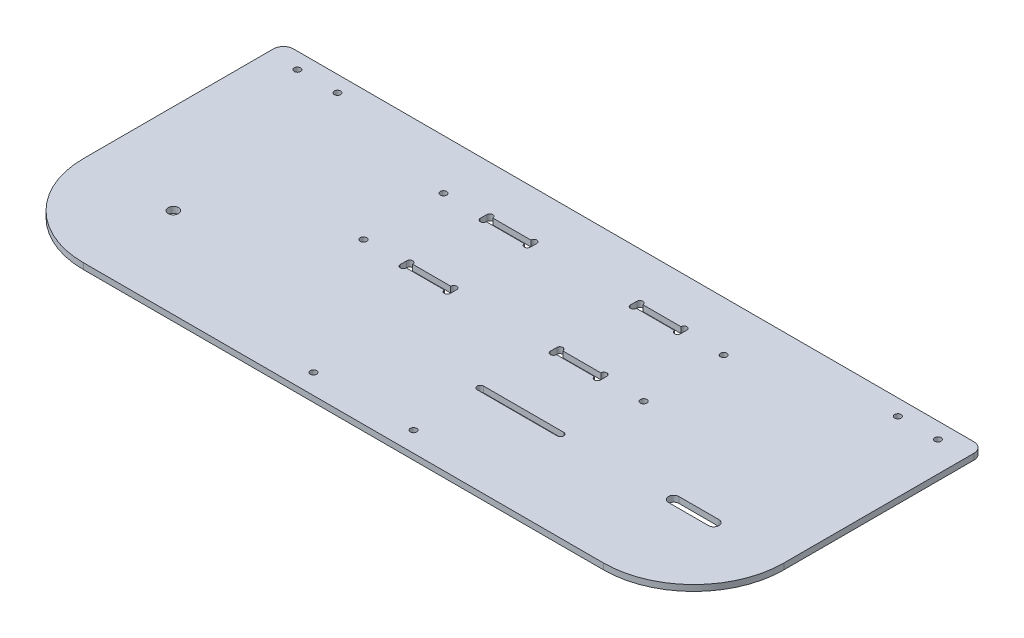
SolidWorks part; units mm, degrees
ref_plane "Front Plane" through (0, 0, 0) normal (0, 0, 1) x (1, 0, 0)
ref_plane "Top Plane" through (0, 0, 0) normal (0, 1, 0) x (1, 0, 0)
ref_plane "Right Plane" through (0, 0, 0) normal (1, 0, 0) x (0, 0, -1)
sketch "Sketch1" plane through (0, 0, 0) normal (0, 1, 0) x (1, 0, 0)
  line L0 (0, 0) -> (260, 0) construction
  line L5 (0, 45) -> (260, 45)
  line L6 (0, -45) -> (260, -45)
  line L7 (270, 0) -> (250, 0) construction
  line L8 (270, -2.6) -> (250, -2.6)
  line L9 (270, 2.6) -> (250, 2.6)
  line L11 (-45, 0) -> (305, 0) construction
  line L12 (-45, 0) -> (-45, 100)
  line L13 (-45, 100) -> (305, 100)
  line L14 (305, 0) -> (305, 100)
  arc A0 (0, 45) -> (0, -45) centre (0, 0) ccw
  arc A1 (260, -45) -> (260, 45) centre (260, 0) ccw
  circle A2 centre (0, 0) radius 2.6
  arc A4 (270, -2.6) -> (270, 2.6) centre (270, 0) ccw
  arc A5 (250, 2.6) -> (250, -2.6) centre (250, 0) ccw
  point P2 (130, 0)
  point P12 (260, 0)
  dimension "D2" = 45
  dimension "D3" = 5.2
  dimension "D1" = 260
  dimension "D4" = 20
  dimension "D5" = 100
  dimension "D6" = 270
extrude "Boss-Extrude1" add sketch "Sketch1" along normal blind 3 contours L6 A1 L5 A0 A5 L9 A4 L8 A2 | A1 L14 L13 L12 A0 L5
sketch "Sketch2" plane through (0, 0, 0) normal (0, -1, 0) x (1, 0, 0)
  line L0 (130, 45) -> (130, -100) construction
  line L1 (80, -73.4) -> (105, -73.4)
  line L2 (80, -73.4) -> (80, -76.6)
  line L3 (80, -76.6) -> (105, -76.6)
  line L4 (105, -73.4) -> (105, -76.6)
  line L5 (0, 45) -> (260, 45) construction
  line L6 (-45, -100) -> (305, -100) construction
  line L7 (-45, -75) -> (305, -75) construction
  line L8 (-45, 0) -> (-45, -100) construction
  line L9 (305, 0) -> (305, -100) construction
  line L10 (81.5, -73.4) -> (81.5, -76.6) construction
  line L11 (83, -73.4) -> (83, -76.6)
  line L12 (80, -73.4) -> (80, -76.6)
  line L13 (103.5, -73.4) -> (103.5, -76.6) construction
  line L14 (105, -73.4) -> (105, -76.6)
  line L15 (102, -73.4) -> (102, -76.6)
  line L16 (-45, -55) -> (305, -55) construction
  line L17 (156.5, -73.4) -> (156.5, -76.6) construction
  line L18 (155, -73.4) -> (155, -76.6)
  line L19 (158, -73.4) -> (158, -76.6)
  line L20 (180, -76.6) -> (155, -76.6)
  line L21 (180, -73.4) -> (155, -73.4)
  line L22 (178.5, -73.4) -> (178.5, -76.6) construction
  line L23 (177, -73.4) -> (177, -76.6)
  line L24 (180, -73.4) -> (180, -76.6)
  line L25 (180, -33.4) -> (155, -33.4)
  line L26 (81.5, -36.6) -> (81.5, -33.4) construction
  line L27 (83, -36.6) -> (83, -33.4)
  line L28 (80, -36.6) -> (80, -33.4)
  line L29 (80, -33.4) -> (105, -33.4)
  line L30 (103.5, -36.6) -> (103.5, -33.4) construction
  line L31 (105, -36.6) -> (105, -33.4)
  line L32 (102, -36.6) -> (102, -33.4)
  line L33 (80, -36.6) -> (105, -36.6)
  line L34 (156.5, -36.6) -> (156.5, -33.4) construction
  line L35 (155, -36.6) -> (155, -33.4)
  line L36 (158, -36.6) -> (158, -33.4)
  line L37 (180, -36.6) -> (155, -36.6)
  line L38 (178.5, -36.6) -> (178.5, -33.4) construction
  line L39 (177, -36.6) -> (177, -33.4)
  line L40 (180, -36.6) -> (180, -33.4)
  line L41 (-45, -92) -> (305, -92) construction
  arc A0 (83, -73.4) -> (80, -73.4) centre (81.5, -73.4) ccw
  arc A1 (80, -76.6) -> (83, -76.6) centre (81.5, -76.6) ccw
  arc A2 (105, -73.4) -> (102, -73.4) centre (103.5, -73.4) ccw
  arc A3 (102, -76.6) -> (105, -76.6) centre (103.5, -76.6) ccw
  arc A4 (155, -73.4) -> (158, -73.4) centre (156.5, -73.4) cw
  arc A5 (158, -76.6) -> (155, -76.6) centre (156.5, -76.6) cw
  arc A6 (177, -73.4) -> (180, -73.4) centre (178.5, -73.4) cw
  arc A7 (180, -76.6) -> (177, -76.6) centre (178.5, -76.6) cw
  arc A8 (83, -36.6) -> (80, -36.6) centre (81.5, -36.6) cw
  arc A9 (80, -33.4) -> (83, -33.4) centre (81.5, -33.4) cw
  arc A10 (105, -36.6) -> (102, -36.6) centre (103.5, -36.6) cw
  arc A11 (102, -33.4) -> (105, -33.4) centre (103.5, -33.4) cw
  arc A12 (155, -36.6) -> (158, -36.6) centre (156.5, -36.6) ccw
  arc A13 (158, -33.4) -> (155, -33.4) centre (156.5, -33.4) ccw
  arc A14 (177, -36.6) -> (180, -36.6) centre (178.5, -36.6) ccw
  arc A15 (180, -33.4) -> (177, -33.4) centre (178.5, -33.4) ccw
  circle A16 centre (-30, -92) radius 1.6
  circle A17 centre (-10, -92) radius 1.6
  circle A18 centre (60, -75) radius 1.6
  circle A19 centre (200, -75) radius 1.6
  circle A20 centre (290, -92) radius 1.6
  circle A21 centre (270, -92) radius 1.6
  circle A22 centre (200, -35) radius 1.6
  circle A23 centre (60, -35) radius 1.6
  point P16 (80, -75)
  point P19 (81.5, -75)
  point P24 (103.5, -75)
  point P35 (156.5, -75)
  point P46 (178.5, -75)
  point P53 (81.5, -35)
  point P62 (103.5, -35)
  point P70 (156.5, -35)
  point P78 (178.5, -35)
  dimension "D5" = 1.5
  dimension "D8" = 3.2
  dimension "D1" = 25
  dimension "D2" = 3.2
  dimension "D3" = 25
  dimension "D4" = 120
  dimension "D6" = 20
  dimension "D7" = 8
  dimension "D9" = 20
  dimension "D10" = 15
  dimension "D11" = 20
extrude "Cut-Extrude1" cut sketch "Sketch2" against normal blind 10 contours L28 L33 L27 L29 | A9 L29 | A8 L33 | L27 L33 L32 L29 | A11 L29 | L32 L33 L31 L29 | A10 L33 | L1 A0 | L11 L1 L2 L3 | L15 L1 L11 L3 | L3 A1 | L1 A2 | L1 L15 L3 L4 | L3 A3 | L25 A13 | L37 L36 L25 L35 | L37 A12 | L37 L39 L25 L36 | L25 A15 | L37 L40 L25 L39 | L37 A14 | A4 L21 | L19 L21 L18 L20 | A5 L20 | L23 L21 L19 L20 | A6 L21 | L24 L21 L23 L20 | A7 L20 | A19 | A20 | A21 | A23 | A18 | A17 | A16 | A22
fillet "Fillet1" radius 5 2 edges at (305, 1.5, -100) (-45, 1.5, -100)
sketch "Sketch3" plane through (0, 0, 0) normal (0, -1, 0) x (1, 0, 0)
  line L0 (270, 0) -> (0, 0) construction
  line L1 (193.4, 0) -> (153.4, 0) construction
  line L2 (193.4, -1.6) -> (153.4, -1.6)
  line L3 (193.4, 1.6) -> (153.4, 1.6)
  line L6 (155, -36.6) -> (155, 45) construction
  line L7 (0, 45) -> (260, 45) construction
  line L8 (105, 35) -> (155, 35) construction
  line L9 (130, -100) -> (130, 45) construction
  line L10 (-40, -100) -> (300, -100) construction
  arc A0 (193.4, -1.6) -> (193.4, 1.6) centre (193.4, 0) ccw
  arc A1 (153.4, 1.6) -> (153.4, -1.6) centre (153.4, 0) ccw
  circle A2 centre (105, 35) radius 1.6
  circle A4 centre (155, 35) radius 1.6
  point P6 (173.4, 0)
  point P19 (130, 35)
  dimension "D3" = 10
  dimension "D4" = 3.2
  dimension "D1" = 3.2
  dimension "D2" = 40
  dimension "D5" = 25
extrude "Cut-Extrude2" cut sketch "Sketch3" against normal through all
sketch "Sketch4" plane through (0, 3, 0) normal (0, 1, 0) x (1, 0, 0)
  line L0 (-45, 0) -> (-45, 95) construction
  line L1 (-45, 84) -> (5.2, 84)
  line L2 (-45, 84) -> (-45, 78.5)
  line L3 (-45, 78.5) -> (5.2, 78.5)
  line L4 (5.2, 84) -> (5.2, 78.5)
  line L5 (130, 100) -> (130, -45) construction
  line L6 (-40, 100) -> (300, 100) construction
  line L7 (0, -45) -> (260, -45) construction
  line L8 (3.7, 84) -> (3.7, 78.5) construction
  line L9 (5.2, 84) -> (5.2, 78.5)
  line L10 (2.2, 84) -> (2.2, 78.5)
  line L11 (256.3, 84) -> (256.3, 78.5) construction
  line L12 (254.8, 84) -> (254.8, 78.5)
  line L13 (257.8, 84) -> (257.8, 78.5)
  line L14 (305, 84) -> (305, 78.5)
  line L15 (305, 78.5) -> (254.8, 78.5)
  line L16 (305, 84) -> (254.8, 84)
  arc A0 (5.2, 84) -> (2.2, 84) centre (3.7, 84) ccw
  arc A1 (2.2, 78.5) -> (5.2, 78.5) centre (3.7, 78.5) ccw
  arc A2 (254.8, 84) -> (257.8, 84) centre (256.3, 84) cw
  arc A3 (257.8, 78.5) -> (254.8, 78.5) centre (256.3, 78.5) cw
  point P14 (3.7, 81.25)
  point P21 (256.3, 81.25)
  dimension "D4" = 1.5
  dimension "D1" = 16
  dimension "D2" = 5.5
  dimension "D3" = 50.2
extrude "Cut-Extrude3" [suppressed] cut sketch "Sketch4" against normal through all contours L10 L1 L2 L3 | L1 L10 L3 L4 | L1 A0 | L3 A1 | A2 L16 | L13 L16 L12 L15 | A3 L15 | L14 L16 L13 L15
fillet "Fillet2" [suppressed] radius 5
